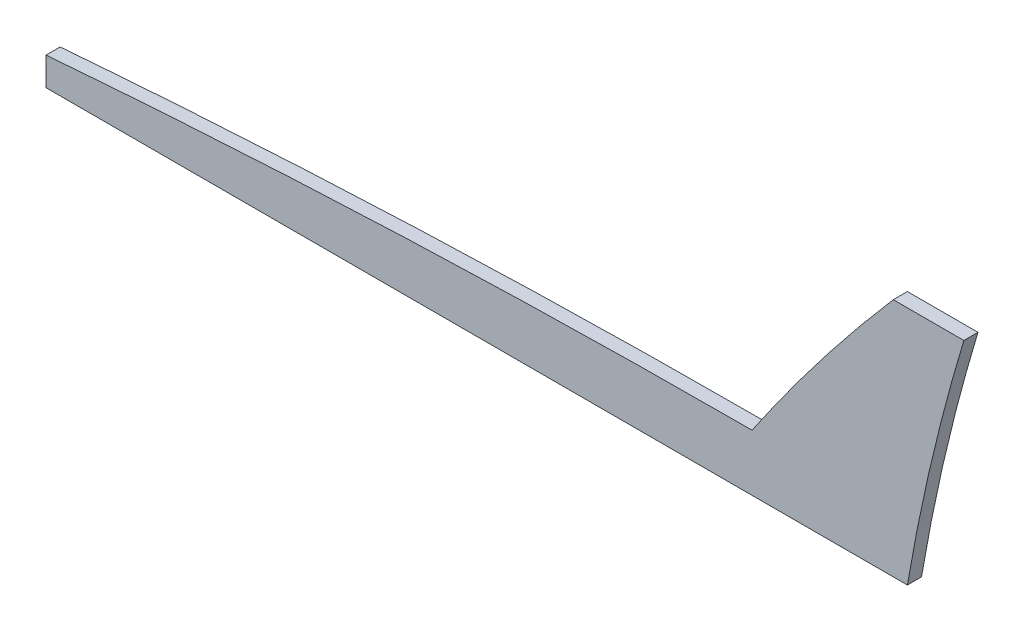
SolidWorks part; units mm, degrees
ref_plane "Front Plane" through (0, 0, 0) normal (0, 0, 1) x (1, 0, 0)
ref_plane "Top Plane" through (0, 0, 0) normal (0, 1, 0) x (1, 0, 0)
ref_plane "Right Plane" through (0, 0, 0) normal (1, 0, 0) x (0, 0, -1)
sketch "Sketch1" plane through (0, 0, 0) normal (0, 0, 1) x (1, 0, 0)
  line L1 (0, 0) -> (0, -20)
  line L2 (600, 150) -> (650, 150)
  line L3 (0, -20) -> (610, -20)
  spline S0 degree 2 poles (-49.8842, -4.1898) (250.0579, 22.1995) (550, 19.8) knots 0 0 0 1 1 1 construction
  spline S1 degree 2 poles (0, 0) (250, 20) (500, 20) knots 0.083156 0.083156 0.083156 0.916651 0.916651 0.916651
  spline S2 degree 2 poles (600, 150) (544.9253, 86.324) (500, 20) knots 0 0 0 1 1 1
  spline S3 degree 2 poles (610, -20) (624.4575, 65.5608) (650, 150) knots 0 0 0 1 1 1
  point P0 (0, 0)
  dimension "D2" = 50
  dimension "D4" = 610
  dimension "D5" = 20
  dimension "D1" = 600
  dimension "D3" = 150
  dimension "D6" = 500
extrude "Boss-Extrude1" add sketch "Sketch1" along normal blind 10
